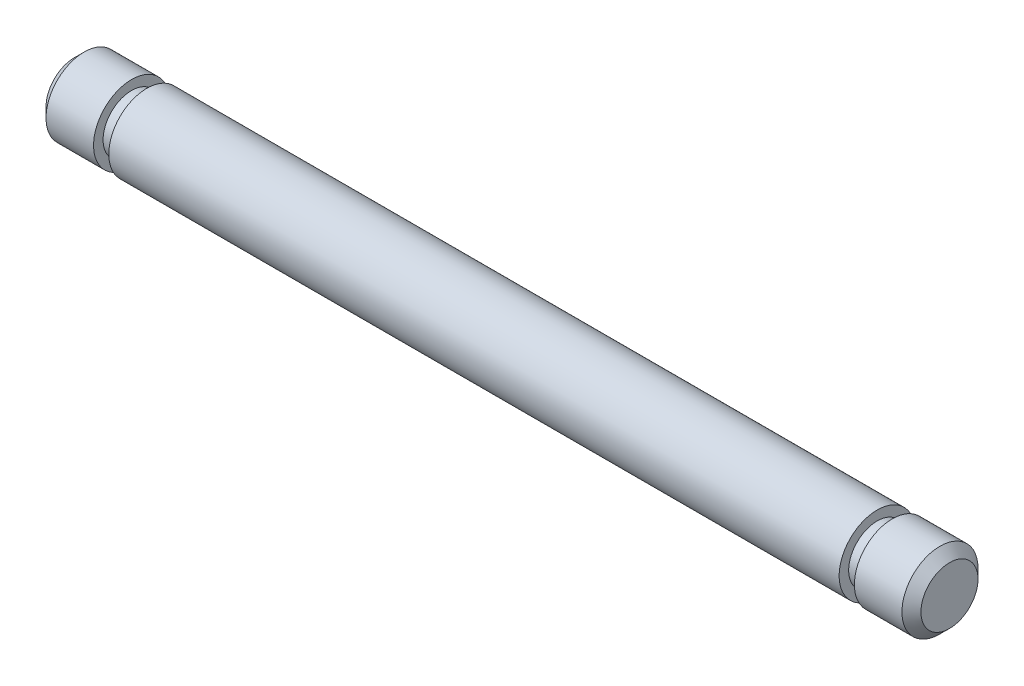
SolidWorks part; units mm, degrees
ref_plane "Front Plane" through (0, 0, 0) normal (0, 0, 1) x (1, 0, 0)
ref_plane "Top Plane" through (0, 0, 0) normal (0, 1, 0) x (1, 0, 0)
ref_plane "Right Plane" through (0, 0, 0) normal (1, 0, 0) x (0, 0, -1)
sketch "Sketch1" plane through (0, 0, 0) normal (1, 0, 0) x (0, 0, -1)
  circle A0 centre (0, 0) radius 2
  dimension "D1" = 4
extrude "Boss-Extrude1" add sketch "Sketch1" along normal mid plane 46
chamfer "Chamfer1" distance 0.5 angle 45 2 edges at (-23, 0, -2) (23, 0, -2)
sketch "Sketch2" plane through (23, 0, 0) normal (1, 0, 0) x (0, 0, -1)
  circle A0 centre (0, 0) radius 2
  circle A1 centre (0, 0) radius 1.5
  dimension "D1" = 3
extrude "Cut-Extrude1" cut sketch "Sketch2" against normal blind 0.8 from offset 3 offset against normal yes
mirror "Mirror1" about plane through (0, 0, 0) normal (1, 0, 0) of "Cut-Extrude1"
